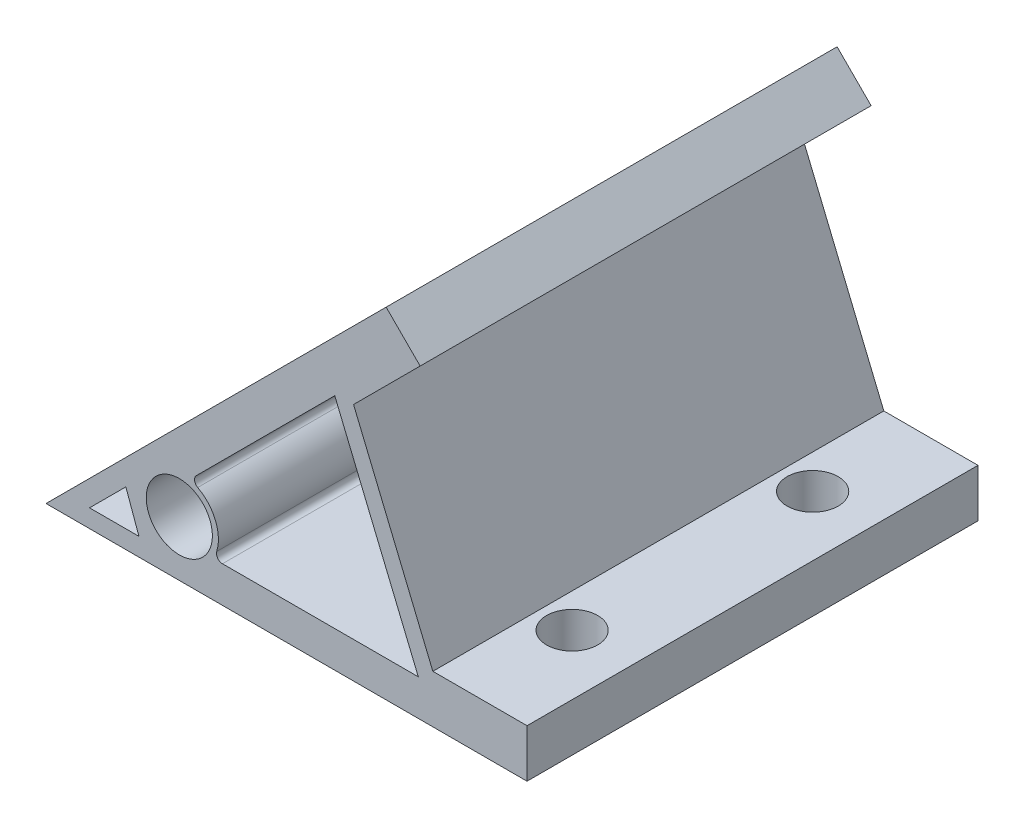
SolidWorks part; units mm, degrees
ref_plane "前视基准面" through (0, 0, 0) normal (0, 0, 1) x (1, 0, 0)
ref_plane "上视基准面" through (0, 0, 0) normal (0, 1, 0) x (1, 0, 0)
ref_plane "右视基准面" through (0, 0, 0) normal (1, 0, 0) x (0, 0, -1)
sketch "草图1" plane through (0, 0, 0) normal (0, 0, 1) x (1, 0, 0)
  line L2 (0, 0) -> (80, 0)
  line L3 (7.2426, 3) -> (15.4571, 3)
  line L4 (64.3352, 8) -> (80, 8)
  line L5 (29.348, 6) -> (61.9164, 6)
  line L6 (0, 0) -> (56.5685, 56.5685)
  line L7 (7.2426, 3) -> (13.2794, 9.0368)
  line L8 (51.1487, 39.835) -> (62.2254, 50.9117)
  line L9 (24.9948, 16.5095) -> (48.0242, 39.5389)
  line L10 (80, 0) -> (80, 8)
  line L11 (56.5685, 56.5685) -> (62.2254, 50.9117)
  line L12 (64.3352, 8) -> (51.1487, 39.835)
  line L13 (61.9164, 6) -> (48.0242, 39.5389)
  line L14 (15.4571, 3) -> (13.2794, 9.0368)
  arc A0 (28.3913, 7.2913) -> (25.2314, 14.92) centre (22.1731, 9.1844) ccw
  arc A1 (24.9948, 16.5095) -> (25.2314, 14.92) centre (25.7019, 15.8024) ccw
  arc A2 (28.3913, 7.2913) -> (29.348, 6) centre (29.348, 7) ccw
  circle A3 centre (22.1731, 9.1844) radius 5.5
extrude "凸台-拉伸1" add sketch "草图1" along normal mid plane 75
sketch "草图2" plane through (0, 0, 0) normal (-0.7071, 0.7071, 0) x (0, 0, 1)
  line L0 (-37.5, 80) -> (37.5, 80) construction
  line L1 (37.5, 80) -> (37.5, 0) construction
  circle A0 centre (20, 70) radius 4.25
  circle A1 centre (-20, 70) radius 4.25
  dimension "D1" = 10
  dimension "D2" = 17.5
  dimension "D3" = 2
extrude "切除-拉伸1" cut sketch "草图2" against normal blind 13
sketch "草图3" plane through (0, 8, 0) normal (0, 1, 0) x (1, 0, 0)
  line L0 (80, 37.5) -> (80, -37.5) construction
  line L1 (80, -37.5) -> (64.3352, -37.5) construction
  circle A0 centre (70, -20) radius 4.25
  circle A1 centre (70, 20) radius 4.25
  dimension "D1" = 10
  dimension "D2" = 17.5
  dimension "D3" = 2
extrude "切除-拉伸2" cut sketch "草图3" against normal through all
